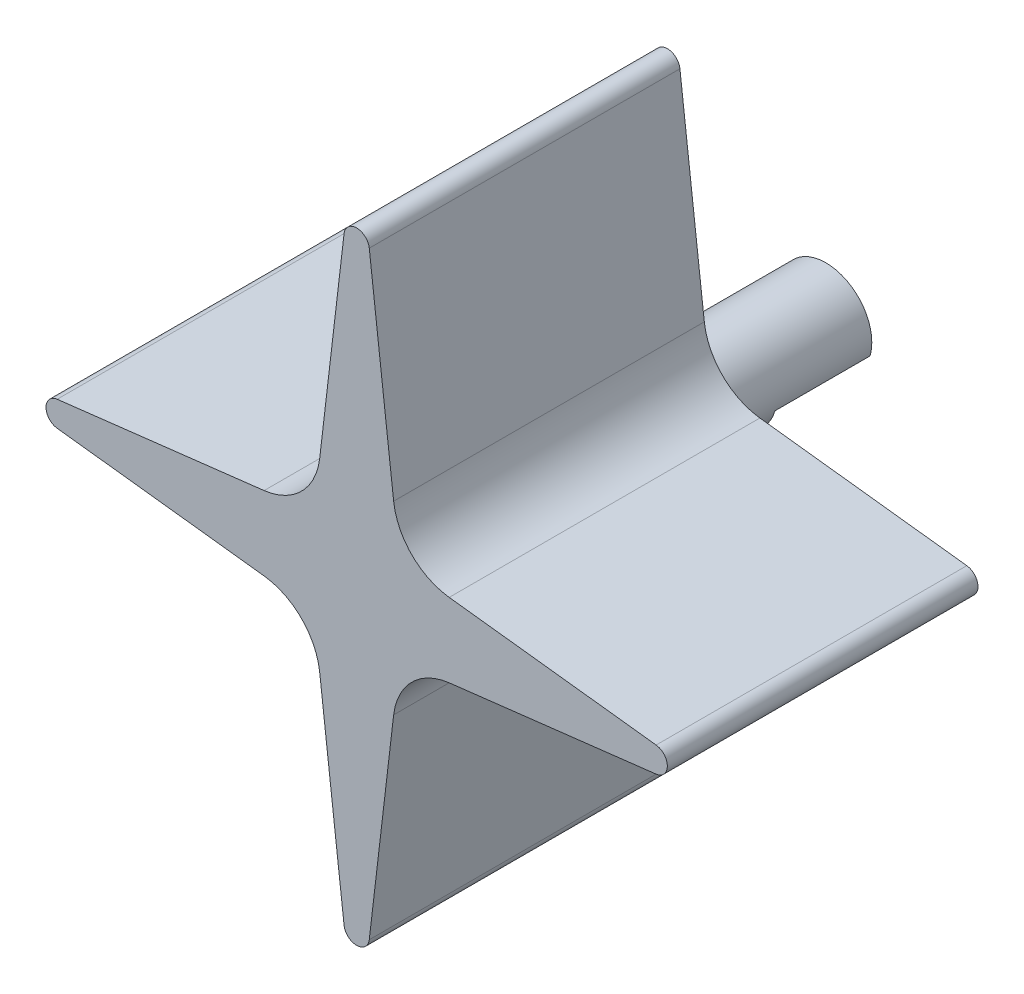
SolidWorks part; units mm, degrees
ref_plane "Front Plane" through (0, 0, 0) normal (0, 0, 1) x (1, 0, 0)
ref_plane "Top Plane" through (0, 0, 0) normal (0, 1, 0) x (1, 0, 0)
ref_plane "Right Plane" through (0, 0, 0) normal (1, 0, 0) x (0, 0, -1)
sketch "Sketch1" plane through (0, 0, 0) normal (0, 0, 1) x (1, 0, 0)
  line L0 (-7.4485, 0.8777) -> (-1.9863, 47.234)
  line L1 (1.9863, 47.234) -> (7.4485, 0.8777)
  line L2 (47.234, -1.9863) -> (0.8777, -7.4485)
  line L3 (0.8777, 7.4485) -> (47.234, 1.9863)
  line L4 (-1.9863, -47.234) -> (-7.4485, -0.8777)
  line L5 (7.4485, -0.8777) -> (1.9863, -47.234)
  line L6 (-47.234, 1.9863) -> (-0.8777, 7.4485)
  line L7 (-0.8777, -7.4485) -> (-47.234, -1.9863)
  circle A0 centre (0, 0) radius 50 construction
  circle A1 centre (0, 0) radius 7.5
  arc A2 (-1.9863, 47.234) -> (1.9863, 47.234) centre (0, 47) cw
  arc A3 (47.234, 1.9863) -> (47.234, -1.9863) centre (47, 0) cw
  arc A4 (1.9863, -47.234) -> (-1.9863, -47.234) centre (0, -47) cw
  arc A5 (-47.234, -1.9863) -> (-47.234, 1.9863) centre (-47, 0) cw
  point P8 (0, 50)
  point P11 (0, 49)
  point P29 (0, 0)
  dimension "D1" = 100
  dimension "D2" = 15
  dimension "D3" = 49
  dimension "D4" = 2
  dimension "D5" = 4
extrude "Boss-Extrude1" add sketch "Sketch1" along normal blind 49 contours A5 L7 L4 A1 L0 L6 | A2 L0 L6 A1 L3 L1 | A3 L3 L1 A1 L5 L2 | A4 L5 L2 A1 L7 L4 | A1 L6 L0 | A1 | A1 L1 L3 | A1 L2 L5 | A1 L4 L7
fillet "Fillet1" radius 10 4 edges at (-6.7558, 6.7558, 24.5) (-6.7558, -6.7558, 24.5) (6.7558, -6.7558, 24.5) (6.7558, 6.7558, 24.5)
sketch "Sketch2" plane through (0, 0, 0) normal (0, 0, -1) x (-1, 0, 0)
  circle A0 centre (0, 0) radius 7.25
  dimension "D1" = 14.5
extrude "Boss-Extrude2" add sketch "Sketch2" along normal blind 25
sketch "Sketch3" plane through (0, 0, -25) normal (0, 0, -1) x (-1, 0, 0)
  line L0 (6.9687, -2) -> (-6.9687, -2)
  circle A0 centre (0, 0) radius 7.25 construction
  arc A1 (6.9687, -2) -> (-6.9687, -2) centre (0, 0) cw
  circle M2 centre (0, 0) radius 7.25
  dimension "D1" = 2
extrude "Cut-Extrude1" cut sketch "Sketch3" against normal blind 15 contours L0 M2
